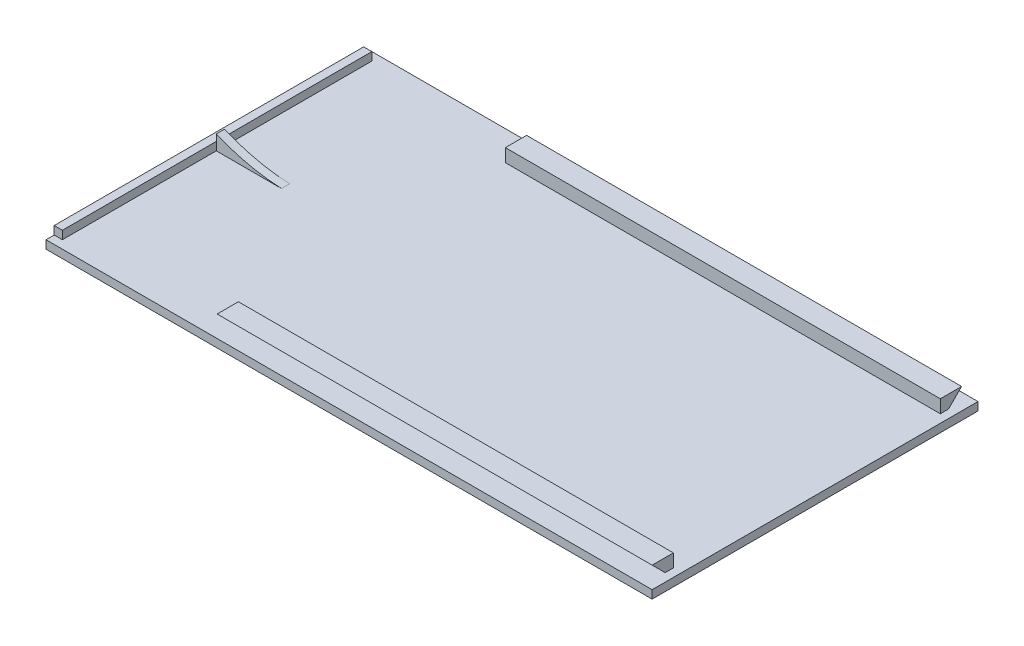
SolidWorks part; units mm, degrees
ref_plane "Plano frontal" through (0, 0, 0) normal (0, 0, 1) x (1, 0, 0)
ref_plane "Plano superior" through (0, 0, 0) normal (0, 1, 0) x (1, 0, 0)
ref_plane "Plano direito" through (0, 0, 0) normal (1, 0, 0) x (0, 0, -1)
sketch "Esboço1" plane through (0, 0, 0) normal (0, 1, 0) x (1, 0, 0)
  line L1 (0, 0) -> (93, 0)
  line L2 (0, 0) -> (0, 50)
  line L3 (0, 50) -> (93, 50)
  line L4 (93, 0) -> (93, 50)
  dimension "D1" = 93
  dimension "D2" = 50
extrude "Ressalto-extrusão1" add sketch "Esboço1" along normal blind 1.26
sketch "Esboço2" plane through (0, 1.26, 0) normal (0, 1, 0) x (1, 0, 0)
  line L0 (0, 50) -> (0, 0) construction
  line L1 (0, 48.74) -> (1.26, 48.74)
  line L2 (0, 48.74) -> (0, 1.26)
  line L3 (0, 1.26) -> (1.26, 1.26)
  line L4 (1.26, 48.74) -> (1.26, 1.26)
  line L5 (93, 50) -> (0, 50) construction
  line L6 (0, 0) -> (93, 0) construction
  dimension "D1" = 1.26
  dimension "D2" = 1.26
  dimension "D3" = 1.26
extrude "Ressalto-extrusão2" add sketch "Esboço2" along normal blind 1.26
sketch "Esboço3" plane through (0, 1.26, 0) normal (0, 1, 0) x (1, 0, 0)
  line L0 (1.26, 1.26) -> (1.26, 48.74) construction
  line L1 (93, 50) -> (0, 50) construction
  line L2 (1.26, 26.13) -> (11.26, 26.13)
  line L3 (1.26, 26.13) -> (1.26, 24.87)
  line L4 (1.26, 24.87) -> (11.26, 24.87)
  line L5 (11.26, 26.13) -> (11.26, 24.87)
  dimension "D1" = 1.26
  dimension "D2" = 10
  dimension "D3" = 23.87
extrude "Ressalto-extrusão3" add sketch "Esboço3" along normal blind 2.26
sketch "Esboço4" plane through (0, 0, -24.87) normal (0, 0, 1) x (1, 0, 0)
  line L0 (1.26, 3.52) -> (11.26, 3.52) construction
  line L1 (1.26, 3.52) -> (11.26, 3.52)
  line L2 (11.26, 3.52) -> (11.26, 1.26)
  arc A0 (1.26, 3.52) -> (11.26, 1.26) centre (12.4759, 29.8941) ccw
  dimension "D1" = 26.3741
extrude "Corte-extrusão1" cut sketch "Esboço4" against normal blind 1.26
sketch "Esboço5" plane through (0, 1.26, 0) normal (0, 1, 0) x (1, 0, 0)
  line L0 (93, 0) -> (93, 50) construction
  line L1 (0, 0) -> (93, 0) construction
  line L2 (25, 1.26) -> (91.74, 1.26)
  line L3 (25, 45.48) -> (91.74, 45.48)
  line L4 (25, 45.48) -> (25, 48.74)
  line L5 (25, 48.74) -> (91.74, 48.74)
  line L6 (91.74, 45.48) -> (91.74, 48.74)
  line L7 (25, 1.26) -> (25, 4.52)
  line L8 (25, 4.52) -> (91.74, 4.52)
  line L9 (91.74, 1.26) -> (91.74, 4.52)
  line L10 (93, 50) -> (0, 50) construction
  dimension "D1" = 1.26
  dimension "D2" = 1.26
  dimension "D3" = 1.26
  dimension "D4" = 1.26
  dimension "D5" = 3.26
  dimension "D6" = 3.26
  dimension "D7" = 66.74
  dimension "D8" = 66.74
extrude "Ressalto-extrusão4" add sketch "Esboço5" along normal blind 2
sketch "Esboço6" plane through (91.74, 0, 0) normal (1, 0, 0) x (0, 0, -1)
  line L0 (3.2622, 1.26) -> (1.26, 3.26)
  line L1 (1.26, 1.26) -> (4.52, 1.26) construction
  line L2 (1.26, 3.26) -> (1.26, 1.26)
  line L3 (1.26, 1.26) -> (3.2622, 1.26)
  line L4 (46.7378, 1.26) -> (48.74, 3.26)
  line L6 (45.48, 1.26) -> (48.74, 1.26) construction
  line L9 (48.74, 3.26) -> (48.74, 1.26)
  line L10 (48.74, 1.26) -> (46.7378, 1.26)
  dimension "D1" = 2.83
  dimension "D2" = 2.83
extrude "Corte-extrusão3" cut sketch "Esboço6" against normal blind 72
